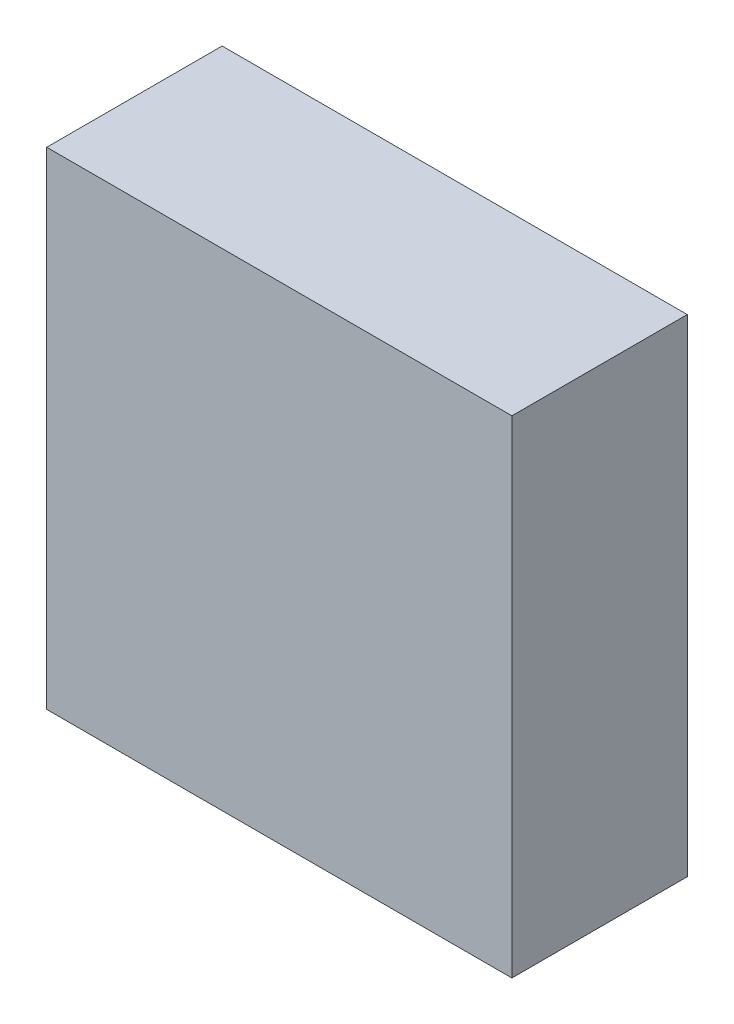
SolidWorks part; units mm, degrees
ref_plane "Front Plane" through (0, 0, 0) normal (0, 0, 1) x (1, 0, 0)
ref_plane "Top Plane" through (0, 0, 0) normal (0, 1, 0) x (1, 0, 0)
ref_plane "Right Plane" through (0, 0, 0) normal (1, 0, 0) x (0, 0, -1)
sketch "Sketch1" plane through (0, 0, 0) normal (0, 0, 1) x (1, 0, 0)
  line L0 (-1.3262, 1.4262) -> (1.3262, 1.4262)
  line L1 (1.3262, 1.4262) -> (1.3262, -1.35)
  line L2 (1.3262, -1.35) -> (-1.3262, -1.35)
  line L3 (-1.3262, -1.35) -> (-1.3262, 1.4262)
extrude "Component_Outline" add sketch "Sketch1" along normal blind 1 separate body
sketch3d "3DSketch1"
  line L0 (0, 0, 0) -> (1, 0, 0)
  line L1 (0, 0, 0) -> (0, 1, 0)
  line L2 (0, 0, 0) -> (0, 0, 1)
  point P0 (0, 0, 0)
